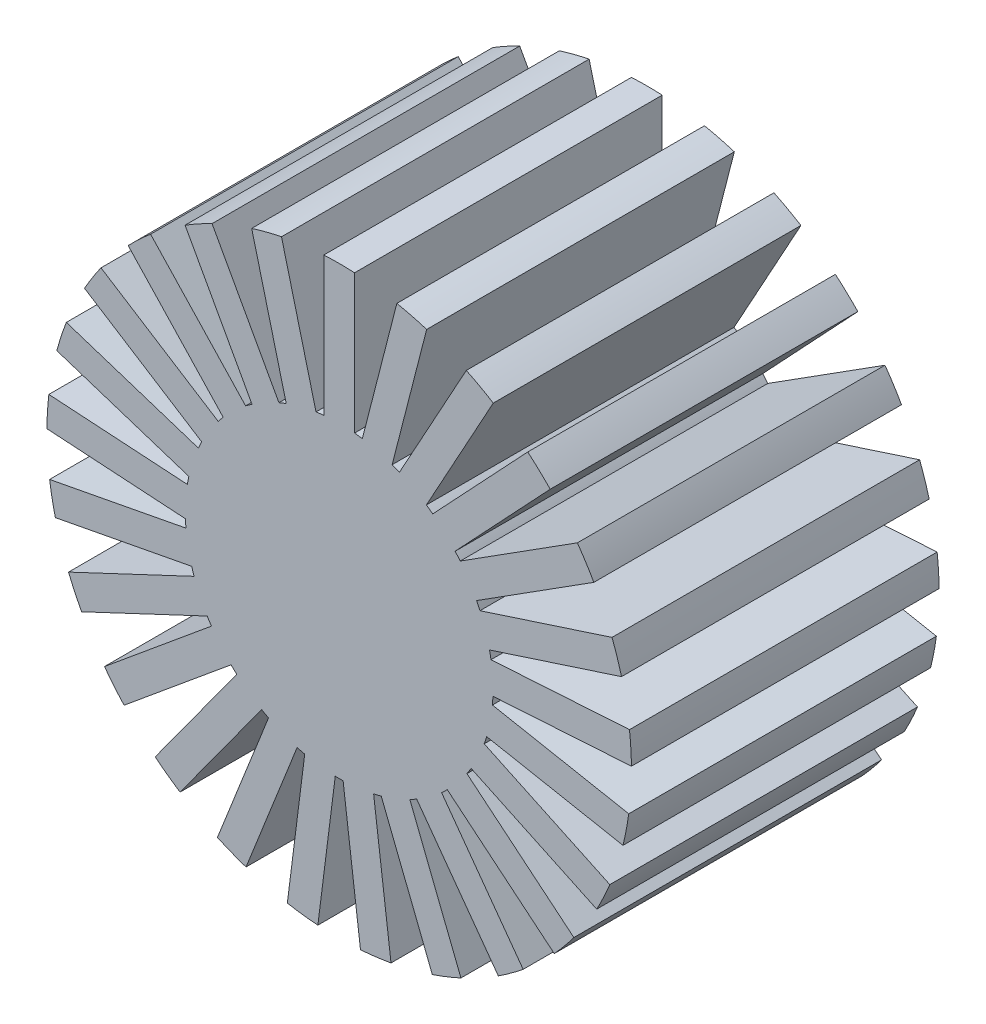
SolidWorks part; units mm, degrees
ref_plane "前视基准面" through (0, 0, 0) normal (0, 0, 1) x (1, 0, 0)
ref_plane "上视基准面" through (0, 0, 0) normal (0, 1, 0) x (1, 0, 0)
ref_plane "右视基准面" through (0, 0, 0) normal (1, 0, 0) x (0, 0, -1)
sketch "草图1" plane through (0, 0, 0) normal (0, 0, 1) x (1, 0, 0)
  line L0 (3.75, 18.6263) -> (1.5058, 9.886)
  line L2 (-1, 18.9737) -> (-1, 9.9499)
  line L4 (1, 18.9737) -> (1, 9.9499)
  line L5 (5.6871, 18.1289) -> (3.443, 9.3886)
  line L6 (8.2643, 17.1085) -> (3.9171, 9.2009)
  line L7 (10.0169, 16.145) -> (5.6697, 8.2374)
  line L8 (12.2594, 14.5158) -> (6.0822, 7.9377)
  line L9 (13.7173, 13.1467) -> (7.5401, 6.5686)
  line L10 (15.4842, 11.0109) -> (7.8651, 6.1757)
  line L11 (16.5558, 9.3223) -> (8.9368, 4.4871)
  line L12 (17.736, 6.8142) -> (9.1539, 4.0257)
  line L13 (18.354, 4.9121) -> (9.7719, 2.1236)
  line L14 (18.8734, 2.1894) -> (9.8675, 1.6228)
  line L15 (18.999, 0.1933) -> (9.993, -0.3733)
  line L16 (18.825, -2.573) -> (9.961, -0.8821)
  line L17 (18.4502, -4.5376) -> (9.5863, -2.8467)
  line L18 (17.5937, -7.1738) -> (9.4287, -3.3316)
  line L19 (16.7421, -8.9834) -> (8.5771, -5.1413)
  line L20 (15.2569, -11.3238) -> (8.3039, -5.5718)
  line L21 (13.982, -12.8648) -> (7.0291, -7.1128)
  line L22 (11.9615, -14.7622) -> (6.6574, -7.4618)
  line L23 (10.3434, -15.9378) -> (5.0394, -8.6374)
  line L24 (7.9144, -17.2731) -> (4.5926, -8.883)
  line L25 (6.0549, -18.0094) -> (2.733, -9.6193)
  line L26 (3.3701, -18.6987) -> (2.2392, -9.7461)
  line L27 (1.3859, -18.9494) -> (0.2549, -9.9967)
  line L28 (-1.3859, -18.9494) -> (-0.2549, -9.9967)
  line L29 (-3.3701, -18.6987) -> (-2.2392, -9.7461)
  line L30 (-6.0549, -18.0094) -> (-2.733, -9.6193)
  line L31 (-7.9144, -17.2731) -> (-4.5926, -8.883)
  line L32 (-10.3434, -15.9378) -> (-5.0394, -8.6374)
  line L33 (-11.9615, -14.7622) -> (-6.6574, -7.4618)
  line L34 (-13.982, -12.8648) -> (-7.0291, -7.1128)
  line L35 (-15.2569, -11.3238) -> (-8.3039, -5.5718)
  line L36 (-16.7421, -8.9834) -> (-8.5771, -5.1413)
  line L37 (-17.5937, -7.1738) -> (-9.4287, -3.3316)
  line L38 (-18.4502, -4.5376) -> (-9.5863, -2.8467)
  line L39 (-18.825, -2.573) -> (-9.961, -0.8821)
  line L40 (-18.999, 0.1933) -> (-9.993, -0.3733)
  line L41 (-18.8734, 2.1894) -> (-9.8675, 1.6228)
  line L42 (-18.354, 4.9121) -> (-9.7719, 2.1236)
  line L43 (-17.736, 6.8142) -> (-9.1539, 4.0257)
  line L44 (-16.5558, 9.3223) -> (-8.9368, 4.4871)
  line L45 (-15.4842, 11.0109) -> (-7.8651, 6.1757)
  line L46 (-13.7173, 13.1467) -> (-7.5401, 6.5686)
  line L47 (-12.2594, 14.5158) -> (-6.0822, 7.9377)
  line L48 (-10.0169, 16.145) -> (-5.6697, 8.2374)
  line L49 (-8.2643, 17.1085) -> (-3.9171, 9.2009)
  line L50 (-5.6871, 18.1289) -> (-3.443, 9.3886)
  line L51 (-3.75, 18.6263) -> (-1.5058, 9.886)
  arc A0 (1, 18.9737) -> (-1, 18.9737) centre (0, 0) ccw
  arc A1 (-1, 9.9499) -> (-1.5058, 9.886) centre (0, 0) ccw
  arc A2 (5.6871, 18.1289) -> (3.75, 18.6263) centre (0, 0) ccw
  arc A3 (10.0169, 16.145) -> (8.2643, 17.1085) centre (0, 0) ccw
  arc A4 (13.7173, 13.1467) -> (12.2594, 14.5158) centre (0, 0) ccw
  arc A5 (16.5558, 9.3223) -> (15.4842, 11.0109) centre (0, 0) ccw
  arc A6 (18.354, 4.9121) -> (17.736, 6.8142) centre (0, 0) ccw
  arc A7 (18.999, 0.1933) -> (18.8734, 2.1894) centre (0, 0) ccw
  arc A8 (18.4502, -4.5376) -> (18.825, -2.573) centre (0, 0) ccw
  arc A9 (16.7421, -8.9834) -> (17.5937, -7.1738) centre (0, 0) ccw
  arc A10 (13.982, -12.8648) -> (15.2569, -11.3238) centre (0, 0) ccw
  arc A11 (10.3434, -15.9378) -> (11.9615, -14.7622) centre (0, 0) ccw
  arc A12 (6.0549, -18.0094) -> (7.9144, -17.2731) centre (0, 0) ccw
  arc A13 (1.3859, -18.9494) -> (3.3701, -18.6987) centre (0, 0) ccw
  arc A14 (-3.3701, -18.6987) -> (-1.3859, -18.9494) centre (0, 0) ccw
  arc A15 (-7.9144, -17.2731) -> (-6.0549, -18.0094) centre (0, 0) ccw
  arc A16 (-11.9615, -14.7622) -> (-10.3434, -15.9378) centre (0, 0) ccw
  arc A17 (-15.2569, -11.3238) -> (-13.982, -12.8648) centre (0, 0) ccw
  arc A18 (-17.5937, -7.1738) -> (-16.7421, -8.9834) centre (0, 0) ccw
  arc A19 (-18.825, -2.573) -> (-18.4502, -4.5376) centre (0, 0) ccw
  arc A20 (-18.8734, 2.1894) -> (-18.999, 0.1933) centre (0, 0) ccw
  arc A21 (-17.736, 6.8142) -> (-18.354, 4.9121) centre (0, 0) ccw
  arc A22 (-15.4842, 11.0109) -> (-16.5558, 9.3223) centre (0, 0) ccw
  arc A23 (-12.2594, 14.5158) -> (-13.7173, 13.1467) centre (0, 0) ccw
  arc A24 (-8.2643, 17.1085) -> (-10.0169, 16.145) centre (0, 0) ccw
  arc A25 (-3.75, 18.6263) -> (-5.6871, 18.1289) centre (0, 0) ccw
  arc A26 (-7.5401, 6.5686) -> (-7.8651, 6.1757) centre (0, 0) ccw
  arc A27 (-5.6697, 8.2374) -> (-6.0822, 7.9377) centre (0, 0) ccw
  arc A28 (-3.443, 9.3886) -> (-3.9171, 9.2009) centre (0, 0) ccw
  arc A29 (-8.9368, 4.4871) -> (-9.1539, 4.0257) centre (0, 0) ccw
  arc A30 (-9.7719, 2.1236) -> (-9.8675, 1.6228) centre (0, 0) ccw
  arc A31 (-9.993, -0.3733) -> (-9.961, -0.8821) centre (0, 0) ccw
  arc A32 (-9.5863, -2.8467) -> (-9.4287, -3.3316) centre (0, 0) ccw
  arc A33 (-8.5771, -5.1413) -> (-8.3039, -5.5718) centre (0, 0) ccw
  arc A34 (-7.0291, -7.1128) -> (-6.6574, -7.4618) centre (0, 0) ccw
  arc A35 (-5.0394, -8.6374) -> (-4.5926, -8.883) centre (0, 0) ccw
  arc A36 (-2.733, -9.6193) -> (-2.2392, -9.7461) centre (0, 0) ccw
  arc A37 (-0.2549, -9.9967) -> (0.2549, -9.9967) centre (0, 0) ccw
  arc A38 (2.2392, -9.7461) -> (2.733, -9.6193) centre (0, 0) ccw
  arc A39 (4.5926, -8.883) -> (5.0394, -8.6374) centre (0, 0) ccw
  arc A40 (6.6574, -7.4618) -> (7.0291, -7.1128) centre (0, 0) ccw
  arc A41 (8.3039, -5.5718) -> (8.5771, -5.1413) centre (0, 0) ccw
  arc A42 (9.4287, -3.3316) -> (9.5863, -2.8467) centre (0, 0) ccw
  arc A43 (9.961, -0.8821) -> (9.993, -0.3733) centre (0, 0) ccw
  arc A44 (9.8675, 1.6228) -> (9.7719, 2.1236) centre (0, 0) ccw
  arc A45 (9.1539, 4.0257) -> (8.9368, 4.4871) centre (0, 0) ccw
  arc A46 (7.8651, 6.1757) -> (7.5401, 6.5686) centre (0, 0) ccw
  arc A47 (6.0822, 7.9377) -> (5.6697, 8.2374) centre (0, 0) ccw
  arc A48 (3.9171, 9.2009) -> (3.443, 9.3886) centre (0, 0) ccw
  arc A49 (1.5058, 9.886) -> (1, 9.9499) centre (0, 0) ccw
  point P4 (0, 10)
  point P7 (2.4869, 9.6858)
  point P15 (4.8175, 8.7631)
  point P20 (6.8455, 7.2897)
  point P25 (8.4433, 5.3583)
  point P30 (9.5106, 3.0902)
  point P35 (9.9803, 0.6279)
  point P40 (9.8229, -1.8738)
  point P45 (9.0483, -4.2578)
  point P50 (7.7051, -6.3742)
  point P55 (5.8779, -8.0902)
  point P60 (3.6812, -9.2978)
  point P65 (1.2533, -9.9211)
  point P70 (-1.2533, -9.9211)
  point P75 (-3.6812, -9.2978)
  point P80 (-5.8779, -8.0902)
  point P85 (-7.7051, -6.3742)
  point P90 (-9.0483, -4.2578)
  point P95 (-9.8229, -1.8738)
  point P100 (-9.9803, 0.6279)
  point P105 (-9.5106, 3.0902)
  point P110 (-8.4433, 5.3583)
  point P115 (-6.8455, 7.2897)
  point P120 (-4.8175, 8.7631)
  point P125 (-2.4869, 9.6858)
  point P130 (0, 0)
  dimension "D1" = 38
  dimension "D2" = 20
  dimension "D3" = 25
extrude "凸台-拉伸1" add sketch "草图1" along normal blind 20
